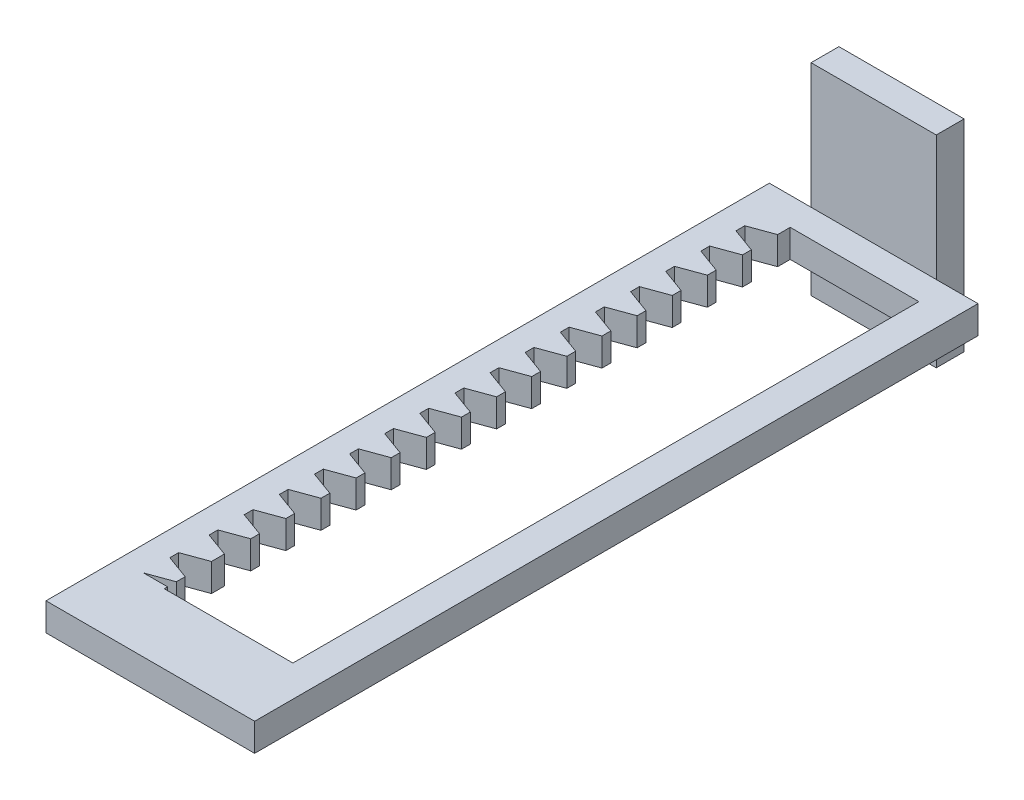
SolidWorks part; units mm, degrees
ref_plane "Alzado" through (0, 0, 0) normal (1, 0, 0) x (0, 1, 0)
ref_plane "Planta" through (0, 0, 0) normal (0, 0, 1) x (0, 1, 0)
ref_plane "Vista lateral" through (0, 0, 0) normal (0, 1, 0) x (-1, 0, 0)
sketch "Croquis1" plane through (0, 0, 0) normal (0, 0, 1) x (0, 1, 0)
  line L1 (-14.5, 9) -> (14.5, 9)
  line L2 (-14.5, 9) -> (-14.5, -9)
  line L3 (-14.5, -9) -> (14.5, -9)
  line L4 (14.5, 9) -> (14.5, -9)
  point P0 (0, 0)
extrude "Saliente-Extruir1" add sketch "Croquis1" along normal blind 4
sketch "Croquis2" plane through (0, 0, 4) normal (0, 0, 1) x (1, 0, 0)
  line L5 (0, 0) -> (0, -14.5)
  line L10 (-9, -14.5) -> (9, -14.5) construction
  line L11 (-15, -7.5) -> (-15, -3.5)
  line L12 (-9, 14.5) -> (-9, -14.5) construction
  line L13 (-9, -7.5) -> (9, -7.5)
  line L14 (9, -14.5) -> (9, 14.5) construction
  line L15 (9, -7.5) -> (15, -7.5)
  line L16 (-9, -7.5) -> (-15, -7.5)
  line L17 (-15, -3.5) -> (15, -3.5)
  line L18 (15, -3.5) -> (15, -7.5)
  line M9 (-9, 14.5) -> (-9, -14.5)
  line M11 (9, -14.5) -> (9, 14.5)
  dimension "D1" = 4
extrude "Saliente-Extruir3" add sketch "Croquis2" along normal blind 4 contours L17 L11 L16 M9 | L17 L13 L5 M9 | L17 L5 L13 M11 | L18 L17 L15 M11
sketch "Croquis4" plane through (0, 0, 8) normal (0, 0, 1) x (1, 0, 0)
  line L0 (-15, -3.5) -> (15, -3.5) construction
  line L1 (15, -7.5) -> (10.5, -7.5)
  line L2 (15, -7.5) -> (15, -3.5)
  line L3 (15, -3.5) -> (10.5, -3.5)
  line L4 (10.5, -7.5) -> (10.5, -3.5)
  dimension "D1" = 4.5
extrude "Saliente-Extruir4" add sketch "Croquis4" along normal blind 100
sketch "Croquis5" plane through (0, 0, 8) normal (0, 0, 1) x (1, 0, 0)
  line L0 (9, -7.5) -> (-9, -7.5) construction
  line L1 (-15, -3.5) -> (-8, -3.5)
  line L2 (-15, -3.5) -> (-15, -7.5)
  line L3 (-15, -7.5) -> (-8, -7.5)
  line L4 (-8, -3.5) -> (-8, -7.5)
extrude "Saliente-Extruir5" add sketch "Croquis5" along normal blind 100
sketch "Croquis6" plane through (0, 0, 108) normal (0, 0, 1) x (1, 0, 0)
  line L1 (-15, -3.5) -> (15, -3.5)
  line L2 (-15, -3.5) -> (-15, -7.5)
  line L3 (-15, -7.5) -> (15, -7.5)
  line L4 (15, -3.5) -> (15, -7.5)
extrude "Saliente-Extruir6" add sketch "Croquis6" against normal blind 10
sketch "Croquis7" plane through (0, -7.5, 0) normal (0, -1, 0) x (1, 0, 0)
  line L0 (-8, 96.2585) -> (-8, 97.5196) construction
  line L2 (-8, 96.2585) -> (-8, 97.5196)
  line L5 (-8, 97.5196) -> (-11.4648, 97.5196)
  line L6 (-11.4648, 97.5196) -> (-8, 97.5196) construction
  line L7 (-11.4648, 97.5196) -> (-8, 96.2585)
  line L8 (-11.4648, 97.5196) -> (-8, 96.2585) construction
extrude "Cortar-Extruir2" cut sketch "Croquis7" against normal blind 10
sketch "Croquis8" plane through (0, -7.5, 0) normal (0, -1, 0) x (-1, 0, 0)
  line L0 (8, -94.9945) -> (11.4648, -93.7334)
  line L2 (8, -97.5196) -> (11.4648, -97.5196) construction
  line L3 (11.4648, -97.5196) -> (8, -96.2585) construction
  line L4 (8, -96.2585) -> (8, -97.5196) construction
  line L5 (8, -94.9945) -> (8, -93.7334) construction
  line L6 (8, -93.7334) -> (11.4648, -93.7334) construction
  line L7 (11.4648, -93.7334) -> (8, -94.9945) construction
  line L8 (11.4648, -93.7334) -> (8, -93.7334)
  line L9 (8, -93.7334) -> (8, -94.9945)
extrude "Cortar-Extruir3" cut sketch "Croquis8" against normal blind 10
sketch "Croquis9" plane through (0, -7.5, 0) normal (0, -1, 0) x (-1, 0, 0)
  line L0 (11.4648, -93.7334) -> (11.4648, -92.4694)
  line L1 (11.4648, -93.7334) -> (8, -93.7334)
  line L2 (8, -93.7334) -> (8, -8) construction
  line L3 (11.4648, -92.4694) -> (8, -91.2083) construction
  line L6 (8, -93.7334) -> (8, -91.2083)
  line L7 (11.4648, -92.4694) -> (8, -91.2083)
extrude "Cortar-Extruir4" cut sketch "Croquis9" against normal blind 10
sketch "Croquis10" plane through (0, -3.5, 0) normal (0, 1, 0) x (-1, 0, 0)
  line L3 (11.4648, 11.0703) -> (8, 9.8092)
  line L4 (11.4648, 12.3343) -> (11.4648, 11.0703)
  line L5 (8, 13.5954) -> (8, 9.8092)
  line L6 (11.4648, 88.0871) -> (8, 89.3482)
  line L7 (11.4648, 88.0871) -> (11.4648, 86.8231)
  line L8 (11.4648, 86.8231) -> (8, 85.562)
  line L9 (8, 89.3482) -> (8, 85.562)
  line L11 (11.4648, 81.7729) -> (8, 80.5118) construction
  line L12 (11.4648, 83.0369) -> (11.4648, 81.7729) construction
  line L13 (8, 84.298) -> (11.4648, 83.0369) construction
  line L15 (8, 75.4616) -> (11.4648, 76.7227) construction
  line L16 (11.4648, 76.7227) -> (11.4648, 77.9867) construction
  line L17 (11.4648, 77.9867) -> (8, 79.2478) construction
  line L19 (11.4648, 71.6725) -> (8, 70.4115) construction
  line L20 (11.4648, 72.9365) -> (11.4648, 71.6725) construction
  line L21 (8, 74.1976) -> (11.4648, 72.9365) construction
  line L23 (8, 65.3613) -> (11.4648, 66.6224) construction
  line L24 (11.4648, 66.6224) -> (11.4648, 67.8864) construction
  line L25 (11.4648, 67.8864) -> (8, 69.1475) construction
  line L26 (11.4648, 61.5722) -> (8, 60.3111) construction
  line L27 (11.4648, 62.8362) -> (11.4648, 61.5722) construction
  line L28 (8, 64.0973) -> (11.4648, 62.8362) construction
  line L29 (8, 55.2609) -> (11.4648, 56.522) construction
  line L30 (11.4648, 56.522) -> (11.4648, 57.786) construction
  line L31 (11.4648, 57.786) -> (8, 59.0471) construction
  line L32 (8, 84.298) -> (11.4648, 83.0369)
  line L33 (8, 53.9969) -> (11.4648, 52.7358) construction
  line L34 (11.4648, 52.7358) -> (11.4648, 51.4718) construction
  line L35 (11.4648, 51.4718) -> (8, 50.2107) construction
  line L36 (11.4648, 83.0369) -> (11.4648, 81.7729)
  line L37 (8, 84.298) -> (8, 80.5118)
  line L38 (8, 80.5118) -> (11.4648, 81.7729)
  line L39 (11.4648, 47.6856) -> (8, 48.9467) construction
  line L40 (11.4648, 46.4216) -> (11.4648, 47.6856) construction
  line L41 (8, 45.1605) -> (11.4648, 46.4216) construction
  line L42 (8, 79.2478) -> (11.4648, 77.9867)
  line L43 (11.4648, 41.3714) -> (8, 40.1103) construction
  line L44 (11.4648, 42.6354) -> (11.4648, 41.3714) construction
  line L45 (8, 43.8965) -> (11.4648, 42.6354) construction
  line L46 (8, 35.0601) -> (11.4648, 36.3212) construction
  line L47 (11.4648, 36.3212) -> (11.4648, 37.5852) construction
  line L48 (11.4648, 37.5852) -> (8, 38.8463) construction
  line L49 (11.4648, 31.271) -> (8, 30.0099) construction
  line L50 (11.4648, 32.535) -> (11.4648, 31.271) construction
  line L51 (8, 33.7961) -> (11.4648, 32.535) construction
  line L52 (8, 24.9597) -> (11.4648, 26.2208) construction
  line L53 (11.4648, 26.2208) -> (11.4648, 27.4848) construction
  line L54 (11.4648, 27.4848) -> (8, 28.7459) construction
  line L55 (11.4648, 21.1706) -> (8, 19.9096) construction
  line L56 (11.4648, 22.4346) -> (11.4648, 21.1706) construction
  line L57 (8, 23.6957) -> (11.4648, 22.4346) construction
  line L58 (8, 14.8594) -> (11.4648, 16.1205) construction
  line L59 (11.4648, 16.1205) -> (11.4648, 17.3845) construction
  line L60 (11.4648, 17.3845) -> (8, 18.6456) construction
  line L61 (11.4648, 77.9867) -> (11.4648, 76.7227)
  line L62 (11.4648, 76.7227) -> (8, 75.4616)
  line L63 (8, 13.5954) -> (11.4648, 12.3343) construction
  line L65 (11.4648, 11.0703) -> (8, 9.8092) construction
  line L66 (8, 75.4616) -> (8, 79.2478)
  line L68 (8, 70.4115) -> (8, 74.1976)
  line L69 (11.4648, 72.9365) -> (11.4648, 71.6725)
  line L70 (11.4648, 71.6725) -> (8, 70.4115)
  line L71 (8, 74.1976) -> (11.4648, 72.9365)
  line L72 (8, 65.3613) -> (8, 69.1475)
  line L73 (8, 69.1475) -> (11.4648, 67.8864)
  line L74 (11.4648, 67.8864) -> (11.4648, 66.6224)
  line L75 (11.4648, 66.6224) -> (8, 65.3613)
  line L76 (8, 60.3111) -> (8, 64.0973)
  line L77 (8, 64.0973) -> (11.4648, 62.8362)
  line L78 (11.4648, 62.8362) -> (11.4648, 61.5722)
  line L79 (11.4648, 61.5722) -> (8, 60.3111)
  line L80 (8, 55.2609) -> (8, 59.0471)
  line L81 (8, 59.0471) -> (11.4648, 57.786)
  line L82 (11.4648, 57.786) -> (11.4648, 56.522)
  line L83 (11.4648, 56.522) -> (8, 55.2609)
  line L84 (8, 50.2107) -> (8, 53.9969)
  line L85 (8, 53.9969) -> (11.4648, 52.7358)
  line L86 (11.4648, 52.7358) -> (11.4648, 51.4718)
  line L87 (11.4648, 51.4718) -> (8, 50.2107)
  line L88 (8, 45.1605) -> (8, 48.9467)
  line L89 (8, 48.9467) -> (11.4648, 47.6856)
  line L90 (11.4648, 47.6856) -> (11.4648, 46.4216)
  line L91 (11.4648, 46.4216) -> (8, 45.1605)
  line L92 (8, 43.8965) -> (11.4648, 42.6354)
  line L93 (11.4648, 42.6354) -> (11.4648, 41.3714)
  line L94 (11.4648, 41.3714) -> (8, 40.1103)
  line L95 (8, 40.1103) -> (8, 43.8965)
  line L96 (8, 38.8463) -> (8, 35.0601)
  line L97 (8, 35.0601) -> (11.4648, 36.3212)
  line L98 (11.4648, 36.3212) -> (11.4648, 37.5852)
  line L99 (11.4648, 37.5852) -> (8, 38.8463)
  line L100 (8, 33.7961) -> (8, 30.0099)
  line L101 (8, 30.0099) -> (11.4648, 31.271)
  line L102 (11.4648, 31.271) -> (11.4648, 32.535)
  line L103 (11.4648, 32.535) -> (8, 33.7961)
  line L104 (8, 24.9597) -> (8, 28.7459)
  line L105 (8, 28.7459) -> (11.4648, 27.4848)
  line L106 (11.4648, 27.4848) -> (11.4648, 26.2208)
  line L107 (11.4648, 26.2208) -> (8, 24.9597)
  line L108 (8, 23.6957) -> (8, 19.9096)
  line L109 (8, 19.9096) -> (11.4648, 21.1706)
  line L110 (11.4648, 21.1706) -> (11.4648, 22.4346)
  line L111 (11.4648, 22.4346) -> (8, 23.6957)
  line L112 (8, 14.8594) -> (8, 18.6456)
  line L113 (8, 18.6456) -> (11.4648, 17.3845)
  line L114 (11.4648, 17.3845) -> (11.4648, 16.1205)
  line L115 (11.4648, 16.1205) -> (8, 14.8594)
  line L117 (8, 13.5954) -> (11.4648, 12.3343)
extrude "Cortar-Extruir5" cut sketch "Croquis10" against normal blind 10
